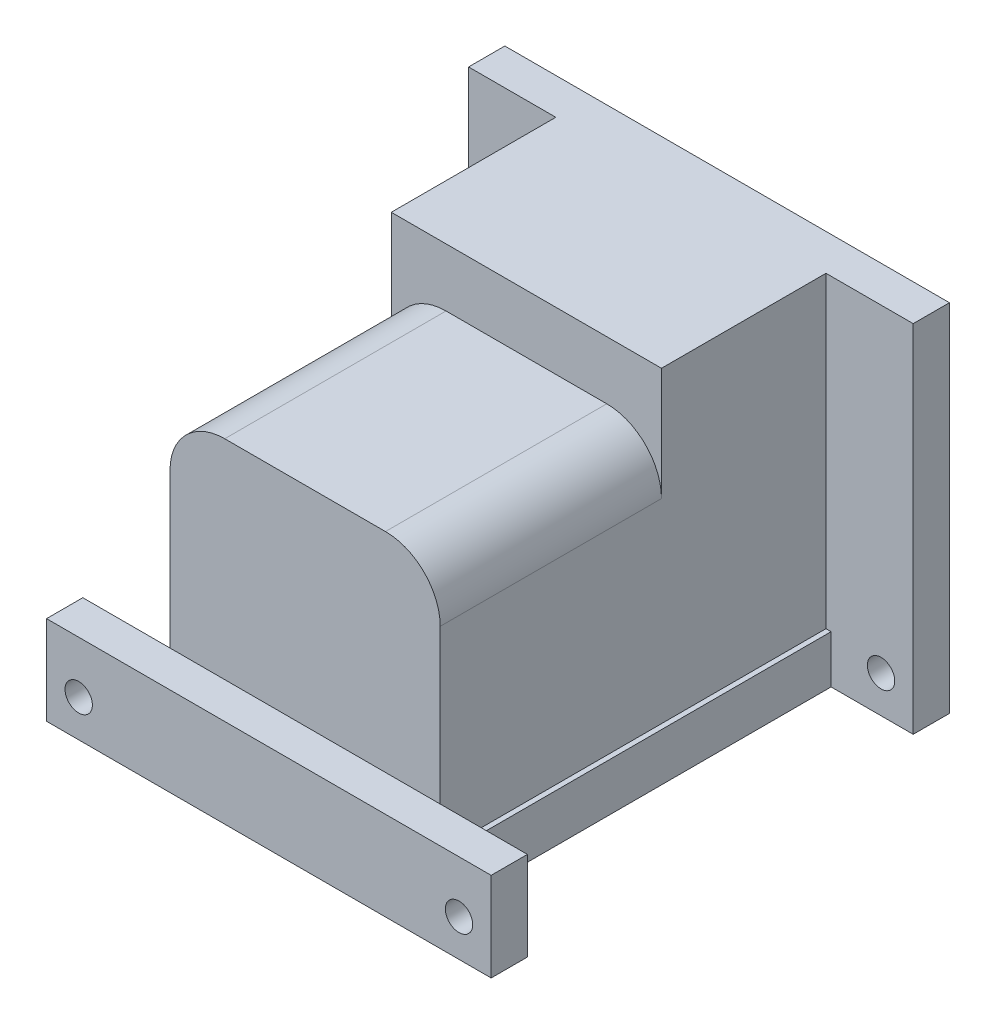
SolidWorks part; units mm, degrees
ref_plane "Plano frontal" through (0, 0, 0) normal (0, 0, 1) x (1, 0, 0)
ref_plane "Plano superior" through (0, 0, 0) normal (0, 1, 0) x (1, 0, 0)
ref_plane "Plano direito" through (0, 0, 0) normal (1, 0, 0) x (0, 0, -1)
sketch "Esboço1" plane through (0, 0, 0) normal (0, 1, 0) x (1, 0, 0)
  line L0 (-32.5, -28.2) -> (-20.5, -28.2)
  line L1 (-32.5, -33.5) -> (32.5, -33.5)
  line L2 (-32.5, -33.5) -> (-32.5, -28.2)
  line L3 (-32.5, 33.5) -> (32.5, 33.5)
  line L4 (32.5, -33.5) -> (32.5, -28.2)
  line L5 (-32.5, -33.5) -> (32.5, 33.5) construction
  line L6 (-32.5, 33.5) -> (32.5, -33.5) construction
  line L7 (-20.5, -28.2) -> (-20.5, 28.2)
  line L8 (-20.5, 28.2) -> (-32.5, 28.2)
  line L9 (32.5, 28.2) -> (20.5, 28.2)
  line L10 (20.5, 28.2) -> (20.5, -28.2)
  line L11 (20.5, -28.2) -> (32.5, -28.2)
  line L12 (32.5, 28.2) -> (32.5, 33.5)
  line L13 (-32.5, 28.2) -> (-32.5, 33.5)
  point P0 (0, 0)
  point P15 (0, 33.5)
  point P16 (0, -33.5)
  dimension "D1" = 67
  dimension "D2" = 5.3
  dimension "D3" = 5.3
  dimension "D4" = 5.3
  dimension "D5" = 65
  dimension "D6" = 12
  dimension "D7" = 12
extrude "Ressalto-extrusão1" add sketch "Esboço1" along normal blind 52
sketch "Esboço2" plane through (0, 0, 33.5) normal (0, 0, 1) x (1, 0, 0)
  line L0 (-32.5, 0) -> (32.5, 0) construction
  line L1 (32.5, 52) -> (32.5, 0) construction
  line L2 (0, -3.7689) -> (0, 14.2309) construction
  circle A0 centre (27.8, 5.4) radius 2
  circle A1 centre (-27.8, 5.4) radius 2
  dimension "D1" = 5.4
  dimension "D2" = 4
  dimension "D3" = 4.7
extrude "Corte-extrusão1" cut sketch "Esboço2" against normal blind 100
sketch "Esboço3" plane through (0, 52, 0) normal (0, 1, 0) x (1, 0, 0)
  line L0 (20.5, 4.15) -> (-20.5, 4.15)
  line L1 (20.5, -28.2) -> (20.5, 28.2) construction
  line L2 (-20.5, 28.2) -> (-20.5, -28.2) construction
  line L3 (-20.5, 4.15) -> (-20.5, -28.2)
  line L4 (-20.5, -28.2) -> (20.5, -28.2)
  line L5 (20.5, -28.2) -> (20.5, 4.15)
  line L6 (-32.5, -33.5) -> (32.5, -33.5) construction
  dimension "D1" = 5.3
  dimension "D2" = 32.35
extrude "Corte-extrusão2" cut sketch "Esboço3" against normal blind 8.5
ref_plane "Plano1" through (0, 52, 0) normal (0, 1, 0) x (1, 0, 0)
sketch "Esboço8" plane through (0, 52, 0) normal (0, 1, 0) x (1, 0, 0)
  line L2 (-32.5, -28.2) -> (-32.5, -33.5)
  line L3 (-32.5, -33.5) -> (32.5, -33.5)
  line L4 (32.5, -33.5) -> (32.5, -28.2)
  line L5 (32.5, -28.2) -> (-32.5, -28.2)
extrude "Corte-extrusão6" cut sketch "Esboço8" against normal blind 39
sketch "Esboço9" plane through (0, 52, 0) normal (0, 1, 0) x (1, 0, 0)
  line L0 (-20.5, 28.2) -> (-19.75, 28.2)
  line L1 (-19.75, 28.2) -> (-19.75, -28.2)
  line L2 (-19.75, -28.2) -> (-20.5, -28.2)
  line L3 (-20.5, -28.2) -> (-20.5, 28.2)
  line L4 (-20.5, 28.2) -> (-20.5, 4.15) construction
  line L5 (0, -37.4701) -> (0, -15.956) construction
  line L6 (20.5, -28.2) -> (-20.5, -28.2) construction
  line L7 (-32.5, 28.2) -> (-20.5, 28.2) construction
  line L8 (20.5, -28.2) -> (20.5, 28.2)
  line L9 (19.75, -28.2) -> (20.5, -28.2)
  line L10 (19.75, 28.2) -> (19.75, -28.2)
  line L11 (20.5, 28.2) -> (19.75, 28.2)
  dimension "D1" = 0.75
  dimension "D2" = 0
extrude "Corte-extrusão7" cut sketch "Esboço9" against normal blind 45
fillet "Filete6" radius 8 2 edges at (19.75, 43.5, 12.025) (-19.75, 43.5, 12.025)
